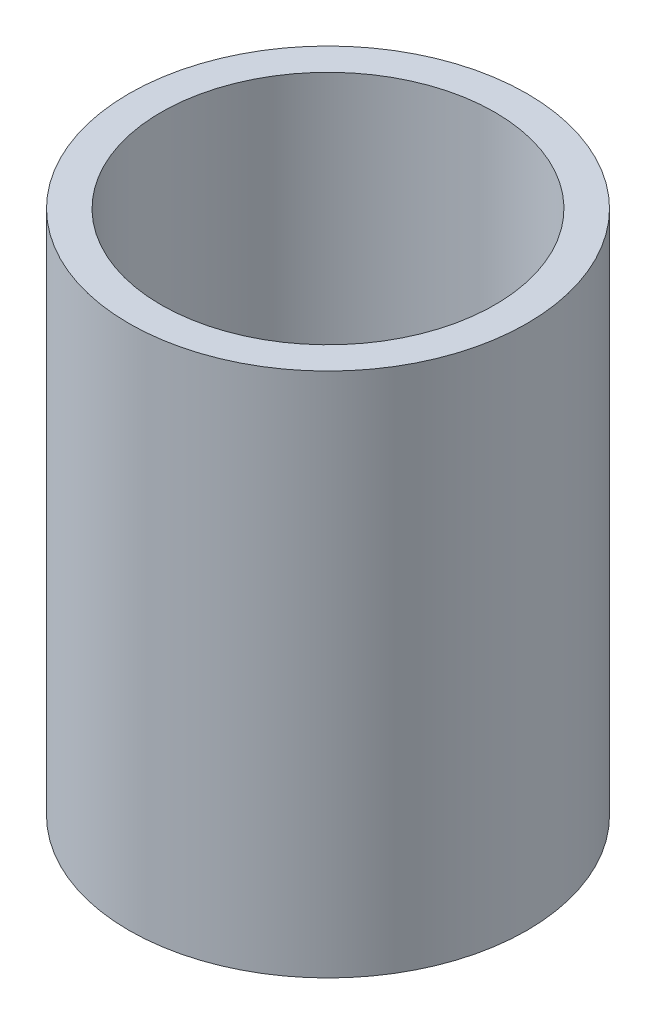
SolidWorks part; units mm, degrees
ref_plane "Front Plane" through (0, 0, 0) normal (0, 0, 1) x (1, 0, 0)
ref_plane "Top Plane" through (0, 0, 0) normal (0, 1, 0) x (1, 0, 0)
ref_plane "Right Plane" through (0, 0, 0) normal (1, 0, 0) x (0, 0, -1)
sketch "Sketch1" plane through (0, 0, 0) normal (0, 1, 0) x (1, 0, 0)
  circle A0 centre (0, 0) radius 30.3
  circle A1 centre (0, 0) radius 25.4
  dimension "D1" = 60.6
  dimension "D2" = 50.8
extrude "Boss-Extrude1" add sketch "Sketch1" along normal blind 80
